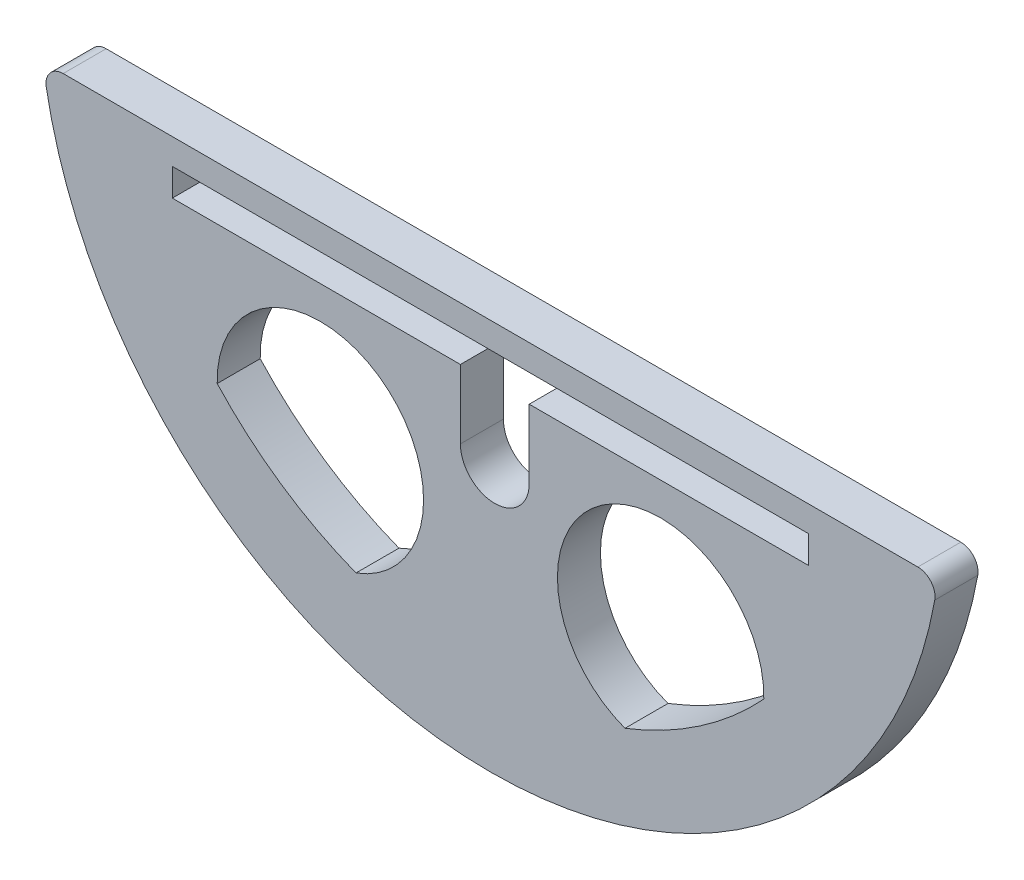
SolidWorks part; units mm, degrees
ref_plane "Alzado" through (0, 0, 0) normal (0, 0, 1) x (1, 0, 0)
ref_plane "Planta" through (0, 0, 0) normal (0, 1, 0) x (1, 0, 0)
ref_plane "Vista lateral" through (0, 0, 0) normal (1, 0, 0) x (0, 0, -1)
sketch "Croquis1" plane through (0, 0, 0) normal (0, 0, 1) x (1, 0, 0)
  line L1 (-37, -1.6) -> (37, -1.6)
  line L2 (-37, -1.6) -> (-37, 1.6)
  line L3 (-37, 1.6) -> (37, 1.6)
  line L4 (37, -1.6) -> (37, 1.6)
  line L5 (-37, -1.6) -> (37, 1.6) construction
  line L6 (-37, 1.6) -> (37, -1.6) construction
  line L7 (-3.5, -9.6) -> (-3.5, -1.6)
  line L8 (4.5, -9.6) -> (4.5, -1.6)
  line L10 (-42, 4.6) -> (42, 4.6)
  line L11 (-42, 4.6) -> (-42, 1.4886)
  line L12 (-40.0475, -4.6) -> (-5.5, -4.6)
  line L13 (42, 4.6) -> (42, 1.4886)
  line L14 (-42, 4.6) -> (40.1297, -4.3952) construction
  line L15 (-40.1297, -4.3952) -> (42, 4.6) construction
  line L16 (-3.5, -4.6) -> (4.5, -4.6)
  line L17 (6.5, -4.6) -> (40.0475, -4.6)
  line L18 (-5.5, -9.6) -> (-5.5, -4.6)
  line L19 (6.5, -9.6) -> (6.5, -4.6)
  line L20 (-49.6915, 4.6) -> (49.6915, 4.6)
  line L21 (-3.5, -14.0721) -> (-3.5, -40.7832)
  line L23 (4.5, -40.7068) -> (4.5, -14.0721)
  circle A0 centre (0.5, -9.6) radius 4
  arc A1 (4.5, -8.1639) -> (-3.5, -8.1639) centre (0.5, -9.6) ccw
  arc A3 (-5.5, -9.6) -> (-3.5, -14.0721) centre (0.5, -9.6) ccw
  arc A4 (4.5, -5.1279) -> (-3.5, -5.1279) centre (0.5, -9.6) ccw
  arc A5 (-42, 1.4886) -> (42, 1.4886) centre (0, 11.6) ccw
  arc A6 (-51.6595, 2.2436) -> (51.6595, 2.2436) centre (0, 11.6) ccw
  arc A7 (-49.6915, 4.6) -> (-51.6595, 2.2436) centre (-49.6915, 2.6) ccw
  arc A8 (51.6595, 2.2436) -> (49.6915, 4.6) centre (49.6915, 2.6) ccw
  arc A9 (4.5, -14.0721) -> (6.5, -9.6) centre (0.5, -9.6) ccw
  point P0 (0, 0)
  point P13 (0, 0)
  dimension "D3" = 8
  dimension "D8" = 8.5
  dimension "D9" = 12
  dimension "D10" = 30
  dimension "D11" = 43.2
  dimension "D12" = 2
  dimension "D13" = 2
  dimension "D1" = 74
  dimension "D2" = 3.2
  dimension "D4" = 37.5
  dimension "D5" = 3
  dimension "D6" = 5
  dimension "D7" = 8
extrude "Saliente-Extruir1" add sketch "Croquis1" along normal blind 5 contours A6 A8 L20 L13 A5 L11 A7 | L11 A5 L12 L18 A3 L19 L17 L13 L10 A0 L7 L1 L2 L3 L4 L8 | L20 A7 A6 L21 A5 L11 | A6 A8 L20 L13 A5 L23
ref_plane "Plano1" through (0, -32.4, 0) normal (0, 1, 0) x (1, 0, 0)
sketch "Croquis3" plane through (0, 0, 0) normal (0, 0, 1) x (1, 0, 0)
  line L1 (0, 0) -> (0, 30.8986) construction
  line L4 (6.5, -4.6) -> (40.0475, -4.6)
  line L5 (-40.0475, -4.6) -> (-5.5, -4.6)
  line L8 (6.5, -9.6) -> (6.5, -4.6)
  line L9 (-5.5, -9.6) -> (-5.5, -4.6)
  line L14 (6.5, -4.6) -> (40.0475, -4.6)
  line L15 (42, 4.6) -> (42, 1.4886)
  line L16 (-40.0475, -4.6) -> (-5.5, -4.6)
  line L17 (-42, 4.6) -> (-42, 1.4886)
  line L18 (-5.5, -31.2485) -> (-5.5, -35.6)
  line L19 (-5.5, -35.6) -> (6.5, -35.6)
  line L20 (6.5, -35.6) -> (6.5, -31.1082)
  arc A0 (-40.0475, -4.6) -> (-31.7804, -17.6617) centre (0, 11.6) ccw
  circle A1 centre (-19.7831, -17.4069) radius 12
  circle A2 centre (19.7831, -17.4069) radius 12
  arc A3 (-15.6406, -28.6692) -> (-13.6103, -29.4) centre (0, 11.6) ccw
  arc A4 (-5.5, -9.6) -> (6.5, -9.6) centre (0.5, -9.6) ccw
  arc A5 (-13.6103, -29.4) -> (-5.5, -31.2485) centre (0, 11.6) ccw
  arc A6 (-42, 1.4886) -> (-31.7804, -17.6617) centre (0, 11.6) ccw
  arc A7 (6.5, -31.1082) -> (40.0475, -4.6) centre (0, 11.6) ccw
  arc A8 (6.5, -31.1082) -> (42, 1.4886) centre (0, 11.6) ccw
  arc A9 (-15.6406, -28.6692) -> (-5.5, -31.2485) centre (0, 11.6) ccw
  dimension "D1" = 24
  dimension "D2" = 43.2
  dimension "D3" = 6
  dimension "D4" = 0.5
  dimension "D8" = 13.6103
  dimension "D6" = 40.0475
  dimension "D7" = 42
  dimension "D11" = 4.6
  dimension "D14" = 9.6
  dimension "D10" = 1.4886
  dimension "D12" = 4
  dimension "D5" = 19.7831
  dimension "D9" = 19.7831
  dimension "D13" = 15.6406
extrude "Saliente-Extruir2" add sketch "Croquis3" along normal up to surface (5 mm away) contours A0 A5 L4 L8 A4 L9 L5 A2 A1
equation "\"D9@Croquis3\"=\"D5@Croquis3\""
